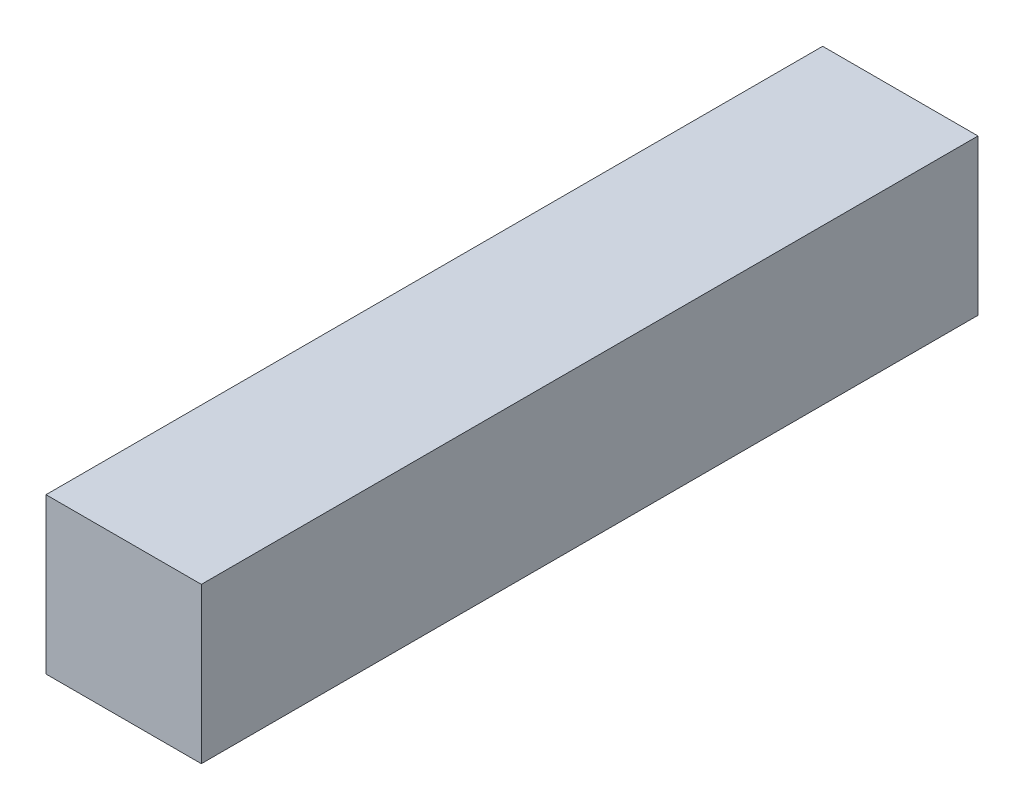
SolidWorks part; units mm, degrees
ref_plane "Front Plane" through (0, 0, 0) normal (0, 0, 1) x (1, 0, 0)
ref_plane "Top Plane" through (0, 0, 0) normal (0, 1, 0) x (1, 0, 0)
ref_plane "Right Plane" through (0, 0, 0) normal (1, 0, 0) x (0, 0, -1)
sketch "Sketch1" plane through (0, 0, 0) normal (0, 0, 1) x (1, 0, 0)
  line L1 (-1.5, -1.5) -> (1.5, -1.5)
  line L2 (-1.5, -1.5) -> (-1.5, 1.5)
  line L3 (-1.5, 1.5) -> (1.5, 1.5)
  line L4 (1.5, -1.5) -> (1.5, 1.5)
  line L5 (-1.5, -1.5) -> (1.5, 1.5) construction
  line L6 (-1.5, 1.5) -> (1.5, -1.5) construction
  point P0 (0, 0)
  dimension "D1" = 3
extrude "Boss-Extrude1" add sketch "Sketch1" along normal blind 15
